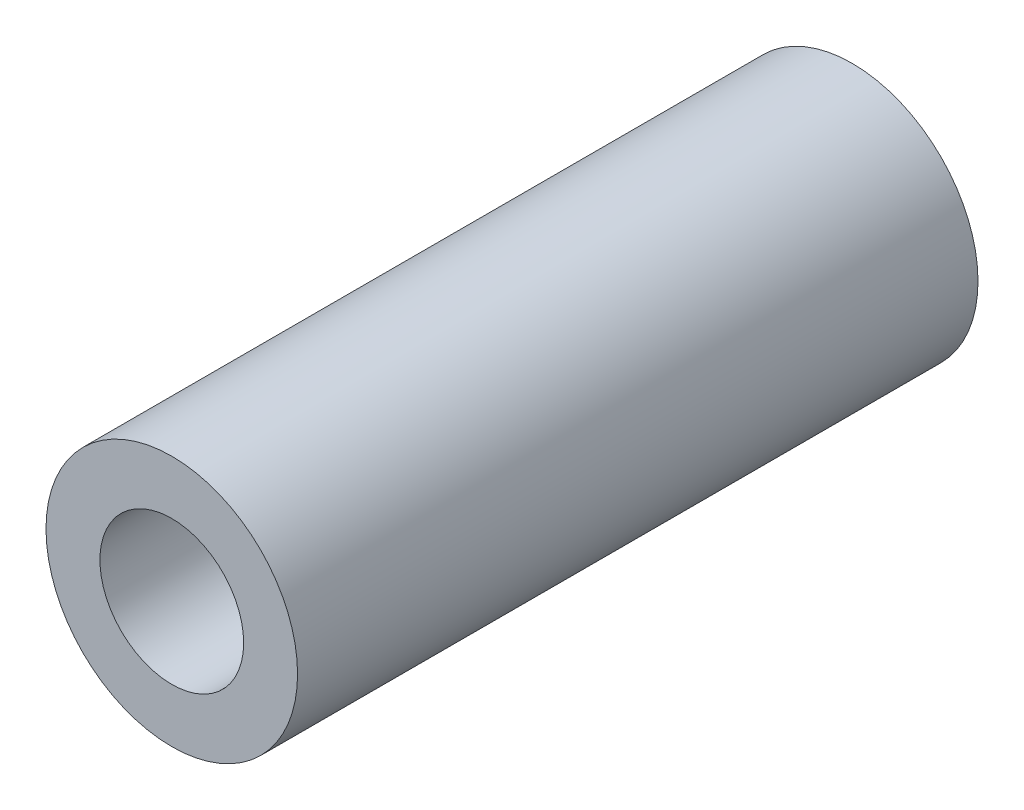
SolidWorks part; units mm, degrees
ref_plane "Front Plane" through (0, 0, 0) normal (0, 0, 1) x (1, 0, 0)
ref_plane "Top Plane" through (0, 0, 0) normal (0, 1, 0) x (1, 0, 0)
ref_plane "Right Plane" through (0, 0, 0) normal (1, 0, 0) x (0, 0, -1)
sketch "Sketch1" plane through (0, 0, 0) normal (0, 0, 1) x (1, 0, 0)
  circle A0 centre (0, 0) radius 6
  circle A1 centre (0, 0) radius 10.5
  dimension "D1" = 12
  dimension "D2" = 21
extrude "Boss-Extrude1" add sketch "Sketch1" along normal blind 56.8
